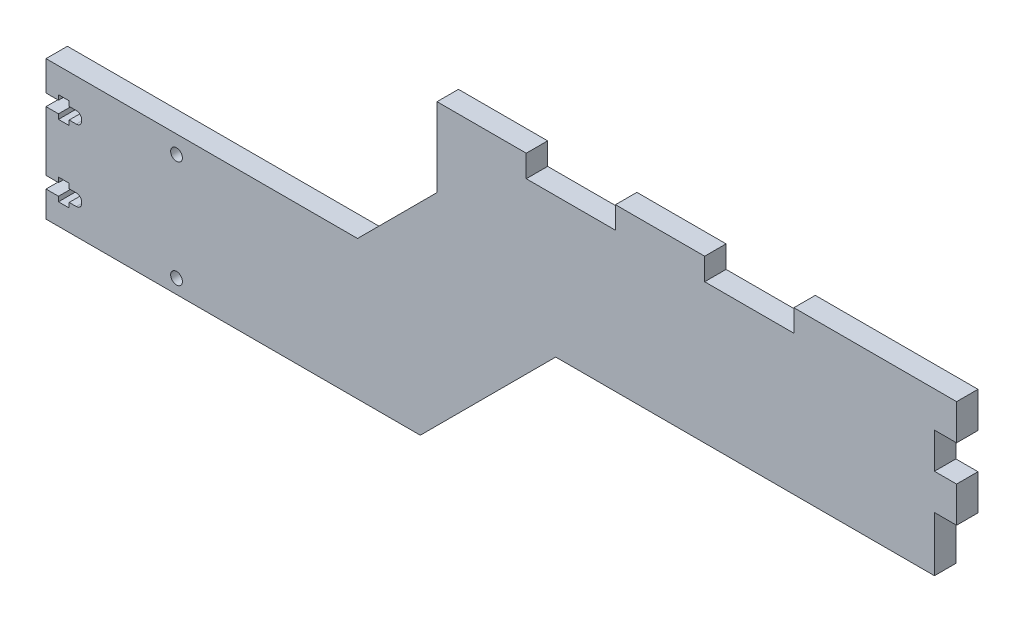
SolidWorks part; units mm, degrees
ref_plane "Спереди" through (0, 0, 0) normal (0, 0, 1) x (1, 0, 0)
ref_plane "Сверху" through (0, 0, 0) normal (0, 1, 0) x (1, 0, 0)
ref_plane "Справа" through (0, 0, 0) normal (1, 0, 0) x (0, 0, -1)
sketch "Эскиз1" plane through (0, 0, 0) normal (0, 0, 1) x (1, 0, 0)
  line L0 (-164.4683, 1.0153) -> (-164.4683, -37.9464)
  line L1 (-54.8861, 45.3538) -> (-54.8861, 23.2989)
  line L2 (-54.8861, 23.2989) -> (-77.1697, 1.0153)
  line L3 (84.5105, 0) -> (-21.6322, 0)
  line L4 (-164.4683, -37.9464) -> (-59.5786, -37.9464)
  line L5 (-77.1697, 1.0153) -> (-164.4683, 1.0153)
  line L7 (90.7105, 35.3538) -> (84.5105, 35.3538)
  line L8 (84.5105, 35.3538) -> (84.5105, 25.3538)
  line L10 (90.7105, 45.3538) -> (45.1139, 45.3538)
  line L11 (-21.6322, 0) -> (-59.5786, -37.9464)
  line L12 (84.5105, 25.3538) -> (90.7105, 25.3538)
  line L13 (90.7105, 25.3538) -> (90.7105, 15.3538)
  line L14 (90.7105, 15.3538) -> (84.5105, 15.3538)
  line L15 (84.5105, 15.3538) -> (84.5105, 0)
  line L16 (90.7105, 35.3538) -> (90.7105, 45.3538)
  line L18 (-29.8861, 45.3538) -> (-29.8861, 39.1538)
  line L19 (-29.8861, 39.1538) -> (-4.8861, 39.1538)
  line L20 (-4.8861, 45.3538) -> (-4.8861, 39.1538)
  line L22 (20.1139, 45.3538) -> (20.1139, 39.1538)
  line L23 (20.1139, 39.1538) -> (45.1139, 39.1538)
  line L24 (45.1139, 39.1538) -> (45.1139, 45.3538)
  line L25 (-29.8861, 45.3538) -> (-54.8861, 45.3538)
  line L26 (20.1139, 45.3538) -> (-4.8861, 45.3538)
  dimension "D1" = 10
  dimension "D8" = 25
  dimension "D2" = 6.2
  dimension "D3" = 10
  dimension "D4" = 10
  dimension "D5" = 25
  dimension "D7" = 25
  dimension "D9" = 25
extrude "Бобышка-Вытянуть1" add sketch "Эскиз1" along normal blind 6
sketch "Эскиз2" plane through (0, 0, 6) normal (0, 0, 1) x (1, 0, 0)
  line L0 (-157.9683, -10.6347) -> (-157.9683, -11.9847)
  line L1 (-160.9683, -5.9847) -> (-157.9683, -5.9847)
  line L2 (-160.9683, -5.9847) -> (-160.9683, -7.3347)
  line L3 (-160.9683, -11.9847) -> (-157.9683, -11.9847)
  line L4 (-157.9683, -5.9847) -> (-157.9683, -7.3347)
  line L6 (-160.9683, -10.6347) -> (-160.9683, -11.9847)
  line L13 (-160.9683, -25.9847) -> (-157.9683, -25.9847)
  line L14 (-160.9683, -25.9847) -> (-160.9683, -27.3347)
  line L15 (-160.9683, -31.9847) -> (-157.9683, -31.9847)
  line L16 (-157.9683, -25.9847) -> (-157.9683, -27.3347)
  line L17 (-157.9683, -30.6347) -> (-155.9683, -30.6347)
  line L23 (-164.4683, -7.3347) -> (-160.9683, -7.3347)
  line L24 (-164.4683, -7.3347) -> (-164.4683, -10.6347)
  line L25 (-164.4683, -10.6347) -> (-160.9683, -10.6347)
  line L26 (-154.4683, -8.8347) -> (-154.4683, -9.1347)
  line L28 (-157.9683, -30.6347) -> (-157.9683, -31.9847)
  line L29 (-157.9683, -10.6347) -> (-155.9683, -10.6347)
  line L30 (-157.9683, -7.3347) -> (-155.9683, -7.3347)
  line L31 (-164.4683, -27.3347) -> (-160.9683, -27.3347)
  line L32 (-164.4683, -27.3347) -> (-164.4683, -30.6347)
  line L33 (-164.4683, -30.6347) -> (-160.9683, -30.6347)
  line L34 (-154.4683, -28.8347) -> (-154.4683, -29.1347)
  line L37 (-160.9683, -30.6347) -> (-160.9683, -31.9847)
  line L38 (-157.9683, -27.3347) -> (-155.9683, -27.3347)
  circle A0 centre (-127.8883, -3.9847) radius 1.65
  arc A1 (-154.4683, -29.1347) -> (-155.9683, -30.6347) centre (-155.9683, -29.1347) cw
  arc A3 (-154.4683, -28.8347) -> (-155.9683, -27.3347) centre (-155.9683, -28.8347) ccw
  arc A5 (-154.4683, -8.8347) -> (-155.9683, -7.3347) centre (-155.9683, -8.8347) ccw
  circle A6 centre (-127.8883, -33.9847) radius 1.65
  arc A7 (-154.4683, -9.1347) -> (-155.9683, -10.6347) centre (-155.9683, -9.1347) cw
  point P0 (-159.4683, -8.9847)
  point P18 (-159.4683, -28.9847)
  point P32 (-159.4683, -28.9847)
  point P35 (-159.4683, -8.9847)
  dimension "D7" = 6
  dimension "D15" = 3.3
  dimension "D9" = 1.5
  dimension "D10" = 1.5
  dimension "D2" = 6
  dimension "D3" = 3
extrude "Вырез-Вытянуть1" cut sketch "Эскиз2" against normal through all
